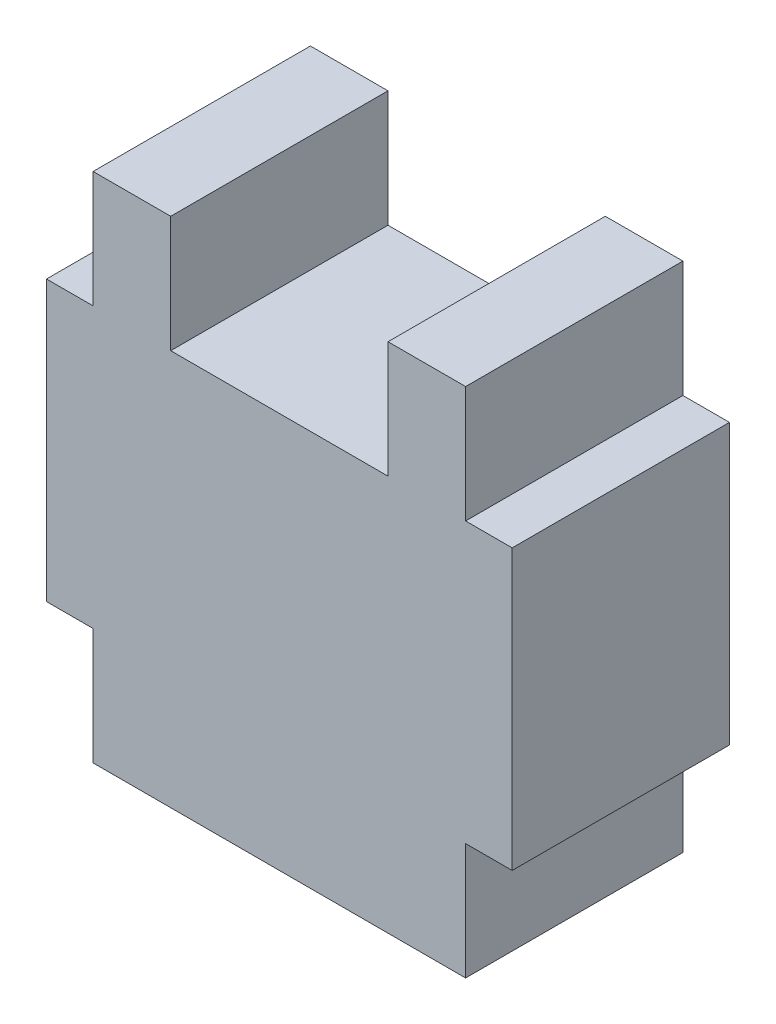
SolidWorks part; units mm, degrees
ref_plane "前视基准面" through (0, 0, 0) normal (0, 0, 1) x (1, 0, 0)
ref_plane "上视基准面" through (0, 0, 0) normal (0, 1, 0) x (1, 0, 0)
ref_plane "右视基准面" through (0, 0, 0) normal (1, 0, 0) x (0, 0, -1)
sketch "草图1" plane through (0, 0, 0) normal (0, 0, 1) x (1, 0, 0)
  line L0 (-1.2, -1.65) -> (-1.2, -0.9)
  line L1 (-1.2, -0.9) -> (-1.5, -0.9)
  line L2 (-1.5, -0.9) -> (-1.5, 0.9)
  line L3 (-1.5, 0.9) -> (-1.2, 0.9)
  line L4 (-1.2, 0.9) -> (-1.2, 1.65)
  line L5 (-1.2, 1.65) -> (-0.7, 1.65)
  line L6 (-0.7, 1.65) -> (-0.7, 0.9)
  line L7 (-0.7, 0.9) -> (0.7, 0.9)
  line L8 (0.7, 0.9) -> (0.7, 1.65)
  line L9 (0.7, 1.65) -> (1.2, 1.65)
  line L10 (1.2, 1.65) -> (1.2, 0.9)
  line L11 (1.2, 0.9) -> (1.5, 0.9)
  line L12 (1.5, 0.9) -> (1.5, -0.9)
  line L13 (1.5, -0.9) -> (1.2, -0.9)
  line L14 (1.2, -0.9) -> (1.2, -1.65)
  line L15 (1.2, -1.65) -> (-1.2, -1.65)
extrude "Component_Outline" add sketch "草图1" along normal blind 1.4 separate body
sketch3d "3D草图1"
  line L0 (0, 0, 0) -> (1, 0, 0)
  line L1 (0, 0, 0) -> (0, 1, 0)
  line L2 (0, 0, 0) -> (0, 0, 1)
  point P0 (0, 0, 0)
